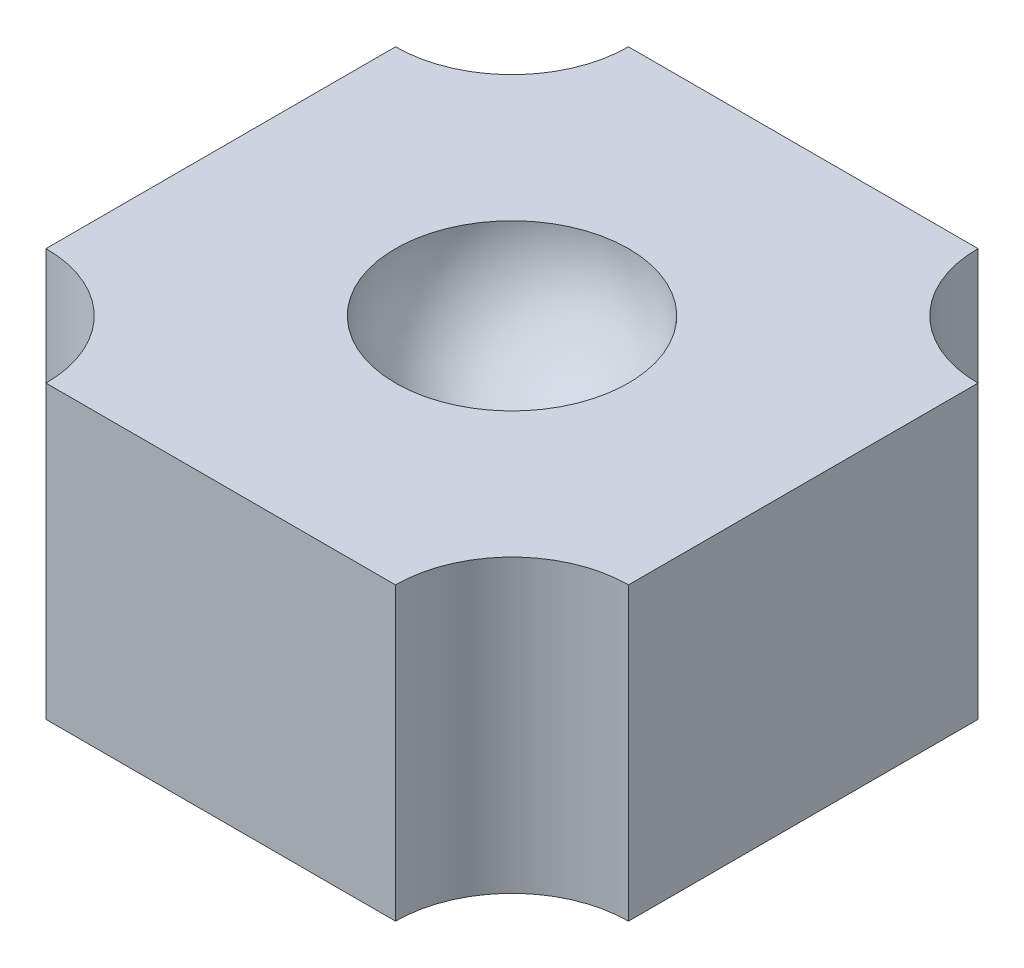
SolidWorks part; units mm, degrees
ref_plane "Front Plane" through (0, 0, 0) normal (0, 0, 1) x (1, 0, 0)
ref_plane "Top Plane" through (0, 0, 0) normal (0, 1, 0) x (1, 0, 0)
ref_plane "Right Plane" through (0, 0, 0) normal (1, 0, 0) x (0, 0, -1)
sketch "Sketch1" plane through (0, 0, 0) normal (0, 1, 0) x (1, 0, 0)
  line L1 (-25, 25) -> (25, 25)
  line L2 (-25, 25) -> (-25, -25)
  line L3 (-25, -25) -> (25, -25)
  line L4 (25, 25) -> (25, -25)
  line L5 (-25, 25) -> (25, -25) construction
  line L6 (-25, -25) -> (25, 25) construction
  point P0 (0, 0)
  dimension "D1" = 50
  dimension "D2" = 50
extrude "Boss-Extrude1" add sketch "Sketch1" along normal blind 25
sketch "Sketch2" plane through (0, 25, 0) normal (0, 1, 0) x (1, 0, 0)
  circle A0 centre (-25, -25) radius 10
  circle A1 centre (-25, 25) radius 10
  circle A2 centre (25, 25) radius 10
  circle A3 centre (25, -25) radius 10
extrude "Cut-Extrude1" cut sketch "Sketch2" against normal blind 25
sketch "Sketch3" plane through (0, 25, 0) normal (0, 1, 0) x (1, 0, 0)
  line L0 (0, 10) -> (0, -10)
  arc A2 (0, 10) -> (0, -10) centre (0, 0) ccw
  dimension "D1" = 10
  dimension "D2" = 20
revolve "Cut-Revolve1" cut sketch "Sketch3" angle 360 about L0
sketch "Sketch4" plane through (0, 0, 0) normal (0, -1, 0) x (-1, 0, 0)
  line L0 (-2.5, 0) -> (-2.5, -7.6699)
  line L1 (-2.5, -7.6699) -> (2.5, -7.6699)
  line L2 (2.5, -7.6699) -> (2.5, 0)
  line L3 (2.5, 0) -> (-2.5, 0)
  circle A0 centre (0, 0) radius 2.5
  circle A1 centre (0, -12) radius 5
  dimension "D1" = 5
  dimension "D2" = 10
  dimension "D3" = 12
sketch "Sketch5" plane through (0, 0, 25) normal (0, 0, 1) x (1, 0, 0)
  line L1 (0, 4.9) -> (-4, 4.9)
  line L2 (0, 4.9) -> (4, 4.9)
  line L3 (-4, 4.9) -> (-4, 8.6)
  line L4 (-4, 8.6) -> (4, 8.6)
  line L5 (4, 8.6) -> (4, 4.9)
  dimension "D1" = 8
  dimension "D4" = 3.7
extrude "Cut-Extrude6" cut sketch "Sketch4" against normal blind 8.6 contours L3 A0 | L3 A0 | A1 L2 A0 L0 | L1 A1 | L1 A1
extrude "Cut-Extrude8" cut sketch "Sketch5" against normal blind 24 from offset 8 offset against normal yes
